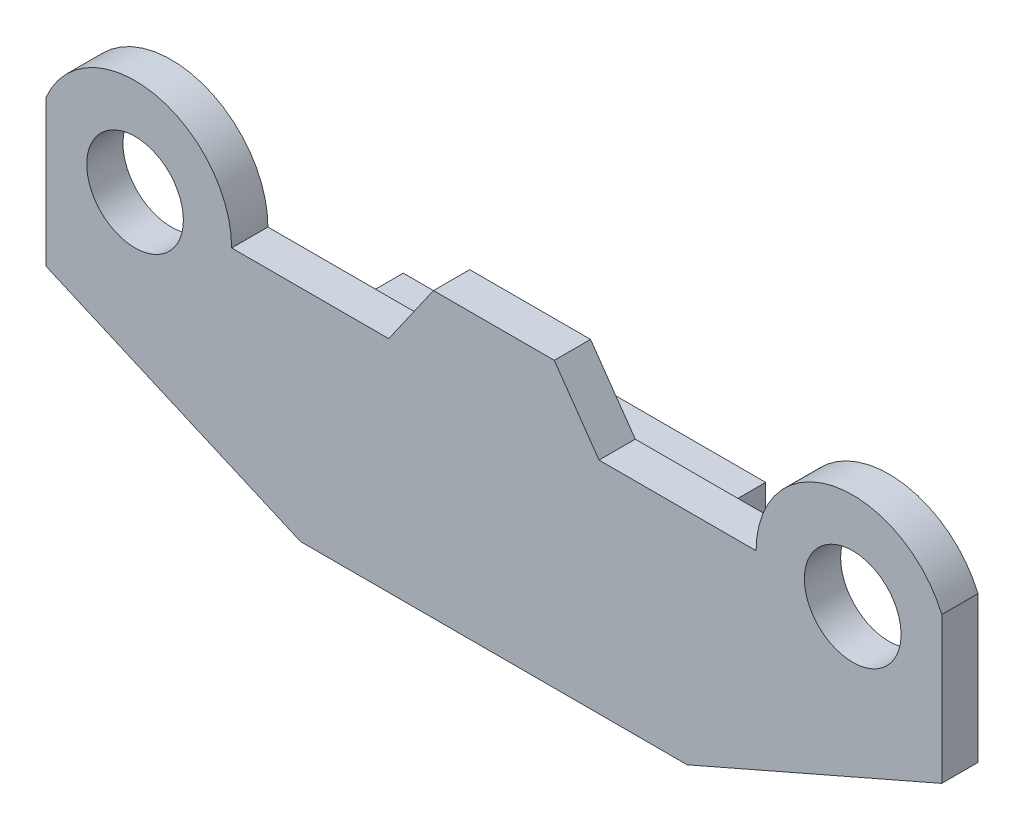
SolidWorks part; units mm, degrees
ref_plane "Front Plane" through (0, 0, 0) normal (0, 0, 1) x (1, 0, 0)
ref_plane "Top Plane" through (0, 0, 0) normal (0, 1, 0) x (1, 0, 0)
ref_plane "Right Plane" through (0, 0, 0) normal (1, 0, 0) x (0, 0, -1)
sketch "Sketch1" plane through (0, 0, 0) normal (0, 0, 1) x (1, 0, 0)
  line L0 (-21.706, 0) -> (-8.706, 0)
  line L1 (-37.0774, 3.1085) -> (-37.0774, -8.9944)
  line L2 (-37.0774, -8.9944) -> (-16, -18.2)
  line L3 (-16, -18.2) -> (16, -18.2)
  line L4 (-37.0774, 0) -> (36.9226, 0) construction
  line L5 (-8.706, 0) -> (-5, 5.3)
  line L6 (-5, 5.3) -> (5, 5.3)
  line L7 (0, 14.1017) -> (0, -30.3848) construction
  line L8 (8.706, 0) -> (5, 5.3)
  line L9 (37.0774, -8.9944) -> (16, -18.2)
  line L10 (37.0774, 3.1085) -> (37.0774, -8.9944)
  line L11 (21.706, 0) -> (8.706, 0)
  arc A0 (-21.706, 0) -> (-37.0774, 3.1085) centre (-29.706, 0) ccw
  circle A1 centre (-29.706, 0) radius 4
  circle A2 centre (29.706, 0) radius 4
  arc A3 (21.706, 0) -> (37.0774, 3.1085) centre (29.706, 0) cw
  point P16 (0, 0)
  point P22 (0, 5.3)
  point P24 (0, -18.2)
  dimension "D7" = 8
  dimension "D1" = 74
  dimension "D3" = 23
  dimension "D4" = 16
  dimension "D5" = 13
  dimension "D6" = 5
  dimension "D8" = 18.2
  dimension "D9" = 23.5
extrude "Boss-Extrude1" add sketch "Sketch1" along normal blind 3
sketch "Sketch2" plane through (0, 0, 0) normal (0, 0, 1) x (1, 0, 0)
  line L0 (0, 0) -> (0, -24.9106) construction
  line L1 (15, -2.2) -> (-15, -2.2)
  line L2 (15, -2.2) -> (15, -17.2)
  line L3 (15, -17.2) -> (-15, -17.2)
  line L4 (-15, -2.2) -> (-15, -17.2)
  line L5 (-16, -18.2) -> (16, -18.2) construction
  point P7 (0, -2.2)
  dimension "D1" = 30
  dimension "D2" = 15
  dimension "D3" = 1
extrude "Boss-Extrude2" add sketch "Sketch2" against normal blind 4.5
